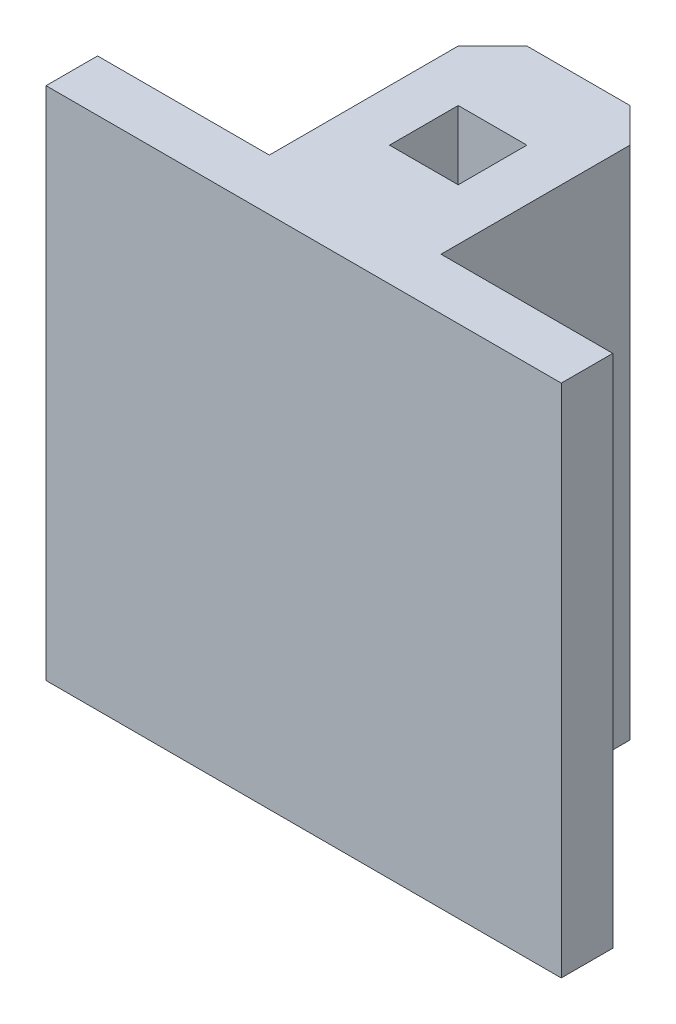
SolidWorks part; units mm, degrees
ref_plane "Front Plane" through (0, 0, 0) normal (0, 0, 1) x (1, 0, 0)
ref_plane "Top Plane" through (0, 0, 0) normal (0, 1, 0) x (1, 0, 0)
ref_plane "Right Plane" through (0, 0, 0) normal (1, 0, 0) x (0, 0, -1)
sketch "Sketch1" plane through (0, 0, 0) normal (0, 1, 0) x (1, 0, 0)
  line L0 (0, 42.9655) -> (0, -67.8751) construction
  line L1 (-70.8097, 0) -> (78.383, 0) construction
  line L2 (-25, 35) -> (25, 35)
  line L3 (-10, -10) -> (10, -10)
  line L4 (-10, -10) -> (-10, 10)
  line L5 (-10, 10) -> (10, 10)
  line L6 (10, -10) -> (10, 10)
  line L7 (-10, -10) -> (10, 10) construction
  line L8 (-10, 10) -> (10, -10) construction
  line L9 (25, 35) -> (25, -30)
  line L10 (25, -30) -> (75, -30)
  line L11 (75, -30) -> (75, -45)
  line L12 (75, -45) -> (-75, -45)
  line L13 (-75, -30) -> (-75, -45)
  line L14 (-25, -30) -> (-75, -30)
  line L15 (-25, 35) -> (-25, -30)
  point P5 (0, 0)
  point P17 (0, -45)
  point P20 (0, 35)
  dimension "D1" = 20
  dimension "D2" = 20
  dimension "D3" = 35
  dimension "D4" = 75
  dimension "D5" = 25
  dimension "D6" = 15
  dimension "D7" = 15
extrude "Boss-Extrude1" add sketch "Sketch1" along normal blind 150
chamfer "Chamfer1" distance 10 angle 45 2 edges at (25, 75, -35) (-25, 75, -35)
